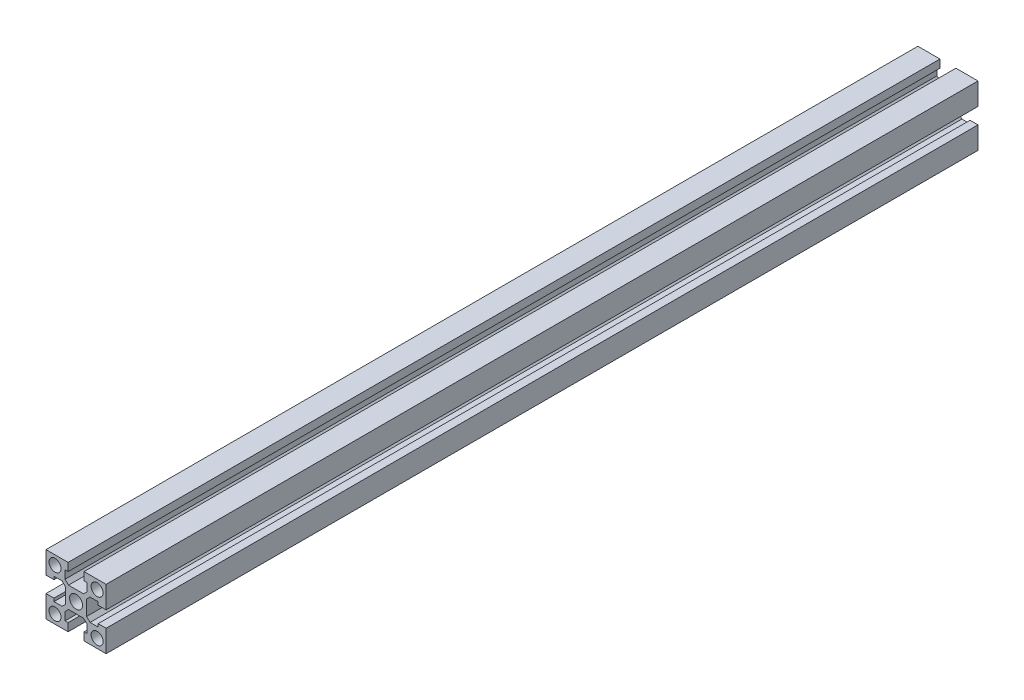
SolidWorks part; units mm, degrees
ref_plane "정면" through (0, 0, 0) normal (0, 0, 1) x (1, 0, 0)
ref_plane "윗면" through (0, 0, 0) normal (0, 1, 0) x (1, 0, 0)
ref_plane "우측면" through (0, 0, 0) normal (1, 0, 0) x (0, 0, -1)
sketch "스케치1" plane through (0, 0, 0) normal (0, 0, 1) x (1, 0, 0)
  line L0 (-10, -10) -> (-2.65, -10)
  line L1 (2.65, -10) -> (10, -10)
  line L2 (10, -10) -> (10, -2.65)
  line L3 (10, 2.65) -> (10, 10)
  line L4 (10, 10) -> (2.65, 10)
  line L5 (-2.65, 10) -> (-10, 10)
  line L6 (-10, 10) -> (-10, 2.65)
  line L7 (-10, -2.65) -> (-10, -10)
  line L8 (0, 10) -> (0, -10) construction
  line L9 (-10, 0) -> (10, 0) construction
  line L10 (2.65, 10) -> (2.65, 7.35)
  line L11 (-2.65, 10) -> (-2.65, 7.35)
  line L12 (-2.5101, 3.5) -> (0, 3.5)
  line L13 (-2.65, 7.35) -> (-3.65, 7.35)
  line L14 (-3.65, 7.35) -> (-3.65, 4.6399)
  line L15 (2.65, 7.35) -> (3.65, 7.35)
  line L16 (2.65, -10) -> (2.65, -7.35)
  line L17 (-2.65, -10) -> (-2.65, -7.35)
  line L18 (0, -3.5) -> (2.5101, -3.5)
  line L19 (-2.65, -7.35) -> (-3.65, -7.35)
  line L20 (2.65, -7.35) -> (3.65, -7.35)
  line L21 (3.65, -7.35) -> (3.65, -4.6399)
  line L22 (-10, 2.65) -> (-7.35, 2.65)
  line L23 (-10, -2.65) -> (-7.35, -2.65)
  line L24 (-3.5, 0) -> (-3.5, 2.5101)
  line L25 (-7.35, -2.65) -> (-7.35, -3.65)
  line L26 (-7.35, 2.65) -> (-7.35, 3.65)
  line L27 (-7.35, 3.65) -> (-4.6399, 3.65)
  line L28 (10, 2.65) -> (7.35, 2.65)
  line L29 (10, -2.65) -> (7.35, -2.65)
  line L30 (3.5, -2.5101) -> (3.5, 0)
  line L31 (7.35, -2.65) -> (7.35, -3.65)
  line L32 (7.35, -3.65) -> (4.6399, -3.65)
  line L33 (7.35, 2.65) -> (7.35, 3.65)
  line L34 (2.5101, -3.5) -> (3.65, -4.6399)
  line L35 (-4.6399, 3.65) -> (-3.5, 2.5101)
  line L36 (-3.65, 4.6399) -> (-2.5101, 3.5)
  line L37 (3.5, -2.5101) -> (4.6399, -3.65)
  line L38 (-2.5101, -3.5) -> (0, -3.5)
  line L39 (-2.65, -7.35) -> (-3.65, -7.35)
  line L40 (-3.65, -7.35) -> (-3.65, -4.6399)
  line L41 (0, 3.5) -> (2.5101, 3.5)
  line L42 (2.65, 7.35) -> (3.65, 7.35)
  line L43 (3.65, 7.35) -> (3.65, 4.6399)
  line L44 (-3.5, 0) -> (-3.5, -2.5101)
  line L45 (-7.35, -2.65) -> (-7.35, -3.65)
  line L46 (-7.35, -3.65) -> (-4.6399, -3.65)
  line L47 (3.5, 2.5101) -> (3.5, 0)
  line L48 (7.35, 2.65) -> (7.35, 3.65)
  line L49 (7.35, 3.65) -> (4.6399, 3.65)
  line L50 (2.5101, 3.5) -> (3.65, 4.6399)
  line L51 (-4.6399, -3.65) -> (-3.5, -2.5101)
  line L52 (-3.65, -4.6399) -> (-2.5101, -3.5)
  line L53 (3.5, 2.5101) -> (4.6399, 3.65)
  circle A0 centre (-7, 7) radius 2
  circle A1 centre (0, 0) radius 2.15
  circle A2 centre (7, 7) radius 2
  circle A3 centre (-7, -7) radius 2
  circle A4 centre (7, -7) radius 2
extrude "보스-돌출1" add sketch "스케치1" along normal mid plane 290 contours L47 L53 L49 L33 L28 L3 L4 L10 L15 L43 L50 L41 L12 L36 L14 L13 L11 L5 L6 L22 L26 L27 L35 L24 L44 L51 L46 L25 L23 L7 L0 L17 L19 L40 L52 L38 L18 L34 L21 L20 L16 L1 L2 L29 L31 L32 L37 L30 A4
